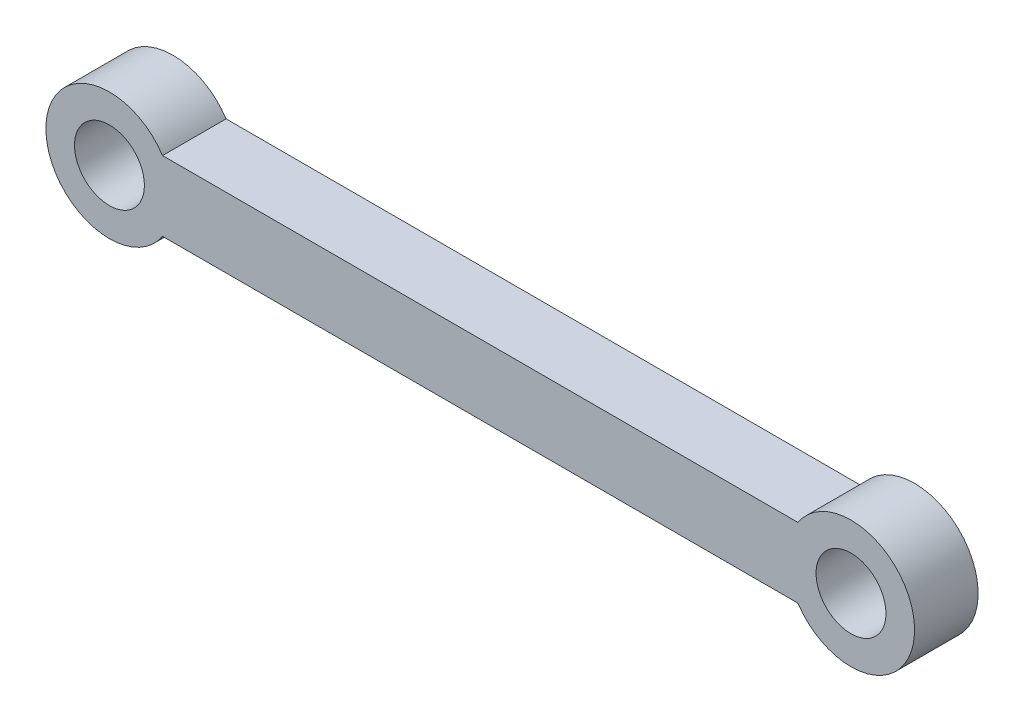
SolidWorks part; units mm, degrees
ref_plane "前视基准面" through (0, 0, 0) normal (0, 0, 1) x (1, 0, 0)
ref_plane "上视基准面" through (0, 0, 0) normal (0, 1, 0) x (1, 0, 0)
ref_plane "右视基准面" through (0, 0, 0) normal (1, 0, 0) x (0, 0, -1)
sketch "草图1" plane through (0, 0, 0) normal (0, 0, 1) x (1, 0, 0)
  line L0 (0, 1.65) -> (35, 1.65)
  line L1 (17.5, -988.0228) -> (17.5, 49011.9772) construction
  line L2 (-1000, 0) -> (49000, 0) construction
  line L3 (0, -1.65) -> (35, -1.65)
  line L4 (35, 1.65) -> (35, -1.65)
  line L5 (0, -1.65) -> (0, 1.65)
  circle A6 centre (0, 0) radius 1.65
  circle A7 centre (0, 0) radius 3
  circle A8 centre (35, 0) radius 3
  circle A9 centre (35, 0) radius 1.65
  dimension "D1" = 3.3
  dimension "D2" = 6
  dimension "D3" = 35
extrude "凸台-拉伸1" add sketch "草图1" along normal blind 3 contours L3 A8 L0 A7 | L3 A7 L0 A6 | L0 A7 L3 A6 | L0 A9 L3 A8 | L3 A9 L0 A8
